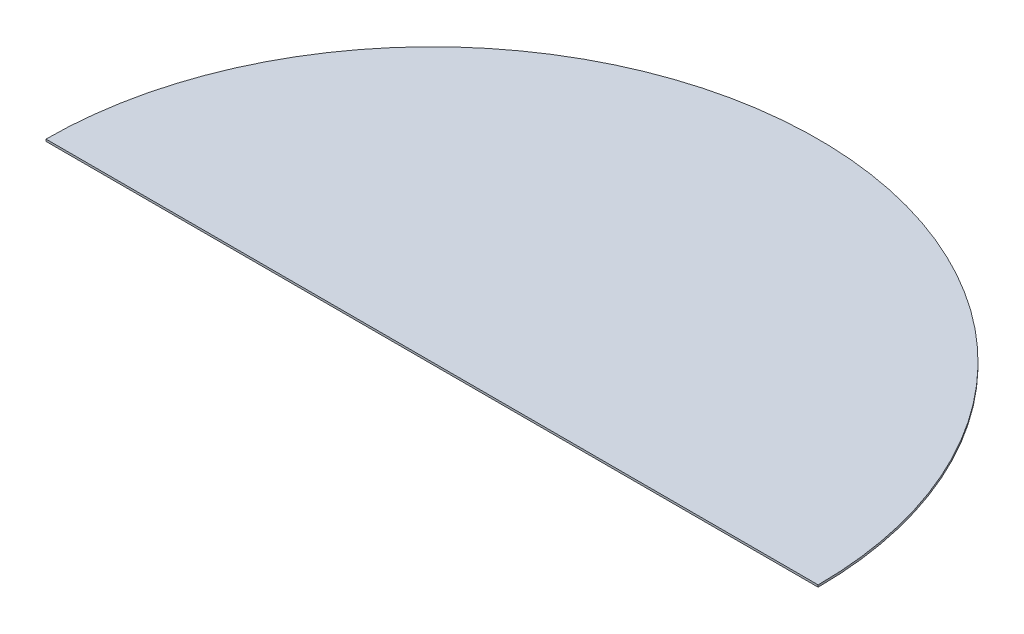
SolidWorks part; units mm, degrees
ref_plane "Front Plane" through (0, 0, 0) normal (0, 0, 1) x (1, 0, 0)
ref_plane "Top Plane" through (0, 0, 0) normal (0, 1, 0) x (1, 0, 0)
ref_plane "Right Plane" through (0, 0, 0) normal (1, 0, 0) x (0, 0, -1)
sketch "Sketch1" plane through (0, 0, 0) normal (0, 1, 0) x (1, 0, 0)
  line L0 (-600, 0) -> (600, 0)
  arc A0 (600, 0) -> (-600, 0) centre (0, 0) ccw
  dimension "D1" = 1200
extrude "Boss-Extrude1" add sketch "Sketch1" along normal blind 3.175
